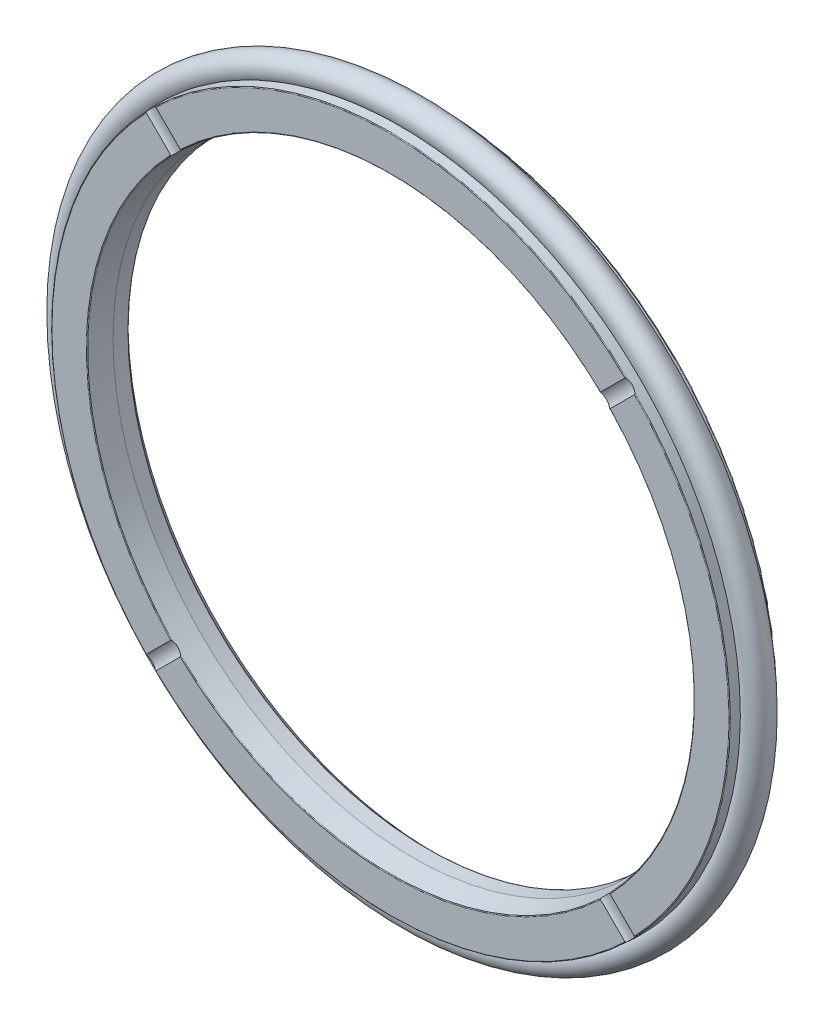
SolidWorks part; units mm, degrees
material "PTFE+NBR"
ref_plane "Front Plane" through (0, 0, 0) normal (0, 0, 1) x (1, 0, 0)
ref_plane "Top Plane" through (0, 0, 0) normal (0, 1, 0) x (1, 0, 0)
ref_plane "Right Plane" through (0, 0, 0) normal (1, 0, 0) x (0, 0, -1)
sketch "Sketch1" plane through (0, 0, 0) normal (1, 0, 0) x (0, 0, -1)
  line L0 (0, 40.75) -> (0, 45.265)
  line L1 (-0.2145, 45.4645) -> (-5.8073, 45.0568)
  line L2 (-5.9, 44.957) -> (-5.9, 40.3857)
  line L3 (-5.8153, 40.2869) -> (-2.9076, 39.8362)
  line L4 (-2.8923, 39.835) -> (-0.9419, 39.835)
  line L5 (-0.8706, 39.8649) -> (0, 40.75)
  line L6 (0, 0) -> (-16.4728, 0) construction
  arc A0 (-0.2145, 45.4645) -> (0, 45.265) centre (-0.2, 45.265) cw
  arc A1 (-0.9419, 39.835) -> (-0.8706, 39.8649) centre (-0.9419, 39.935) ccw
  arc A2 (-2.9076, 39.8362) -> (-2.8923, 39.835) centre (-2.8923, 39.935) ccw
  arc A3 (-5.9, 40.3857) -> (-5.8153, 40.2869) centre (-5.8, 40.3857) ccw
  arc A4 (-5.8073, 45.0568) -> (-5.9, 44.957) centre (-5.8, 44.957) ccw
  point P13 (-0.9, 39.835)
  point P16 (-2.9, 39.835)
  point P19 (-5.9, 40.3)
  point P22 (-5.9, 45.05)
  dimension "D2" = 0.2
  dimension "D4" = 90.93
  dimension "D10" = 0.1
  dimension "D1" = 5.9
  dimension "D3" = 90.1
  dimension "D5" = 79.67
  dimension "D6" = 81.5
  dimension "D7" = 0.9
  dimension "D8" = 3
  dimension "D9" = 80.6
revolve "Revolve1" add sketch "Sketch1" angle 360 about L6
sketch "Sketch2" plane through (0, 0, 0) normal (1, 0, 0) x (0, 0, -1)
  line L0 (0, 0) -> (14.1525, 0) construction
  line L1 (0, -45.265) -> (0, 45.265) construction
  line L2 (0, 0.9) -> (0, -0.9)
  arc A0 (0, 0.9) -> (0, -0.9) centre (1.495, 0) ccw
  dimension "D1" = 0.25
  dimension "D2" = 1.8
extrude "Cut-Extrude1" cut sketch "Sketch2" against normal through all and the other way through all
ref_axis "Axis1" through (0, 0, -19.1174) along (0, 0, 1)
pattern_circular "CirPattern1" count 4 over 360 about axis through (0, 0, -19.1174) along (0, 0, 1) of "Cut-Extrude1"
ref_plane "Plane1" through (0, 0, 0) normal (0.7071, -0.7071, 0) x (0.7071, 0.7071, 0)
sketch "Sketch3" plane through (0, 0, 0) normal (0.7071, -0.7071, 0) x (0.7071, 0.7071, 0)
  line L0 (0, 0) -> (0, 13.0703) construction
  line L1 (-0.9, 5.9) -> (0.9, 5.9)
  line L2 (44.957, 5.9) -> (-44.957, 5.9) construction
  arc A0 (-0.9, 5.9) -> (0.9, 5.9) centre (0, 7.395) ccw
  dimension "D1" = 0.25
  dimension "D2" = 1.8
extrude "Cut-Extrude2" cut sketch "Sketch3" against normal through all and the other way through all
pattern_circular "CirPattern2" count 4 over 360 about axis through (0, 0, -19.1174) along (0, 0, 1) of "Cut-Extrude2"
sketch "Sketch4" plane through (0, 0, 0) normal (1, 0, 0) x (0, 0, -1)
  line L0 (0, 0) -> (-15.9616, 0) construction
  line L1 (-3.0286, 45.2593) -> (-3.0286, 46.7707) construction
  line L2 (-0.25, 45.4619) -> (-5.8073, 45.0568) construction
  circle A0 centre (-3.0286, 46.015) radius 1.765
  dimension "D1" = 3.53
  dimension "D2" = 88.5
revolve "Revolve2" add sketch "Sketch4" angle 360 about L0
